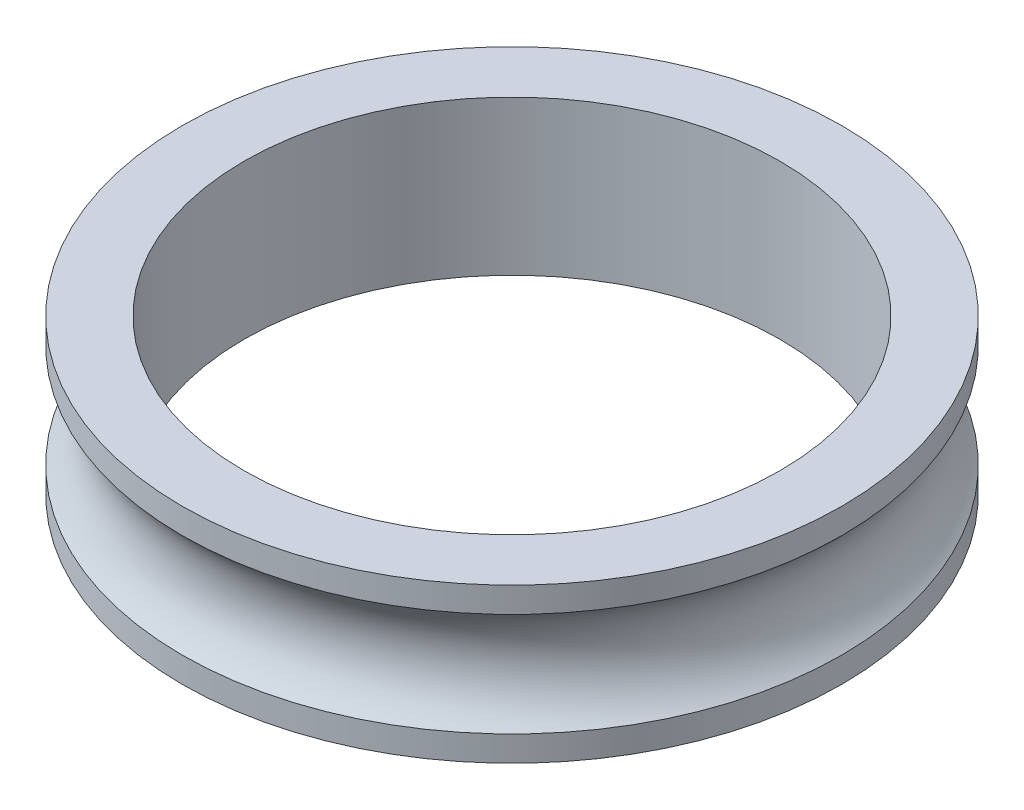
SolidWorks part; units mm, degrees
ref_plane "前视基准面" through (0, 0, 0) normal (0, 0, 1) x (1, 0, 0)
ref_plane "上视基准面" through (0, 0, 0) normal (0, 1, 0) x (1, 0, 0)
ref_plane "右视基准面" through (0, 0, 0) normal (1, 0, 0) x (0, 0, -1)
other "Configuration Table"
sketch "草图1" plane through (0, 0, 0) normal (0, 0, 1) x (1, 0, 0)
  line L0 (34.75, 10) -> (34.75, -10)
  line L1 (34.75, -10) -> (42.75, -10)
  line L2 (34.75, 10) -> (42.75, 10)
  line L3 (0, 0) -> (289.7303, 0) construction
  line L4 (42.75, 10) -> (42.75, 6.7082)
  line L5 (42.75, -6.7082) -> (42.75, -10)
  line L6 (0, 53.3742) -> (0, -37.2884) construction
  arc A0 (42.75, 6.7082) -> (42.75, -6.7082) centre (48.75, 0) ccw
  point P10 (39.75, 0)
  dimension "D2" = 8
  dimension "D1" = 18
  dimension "D3" = 20
  dimension "D4" = 3
  dimension "D5" = 48.75
revolve "旋转1" add sketch "草图1" angle 360 about L6
